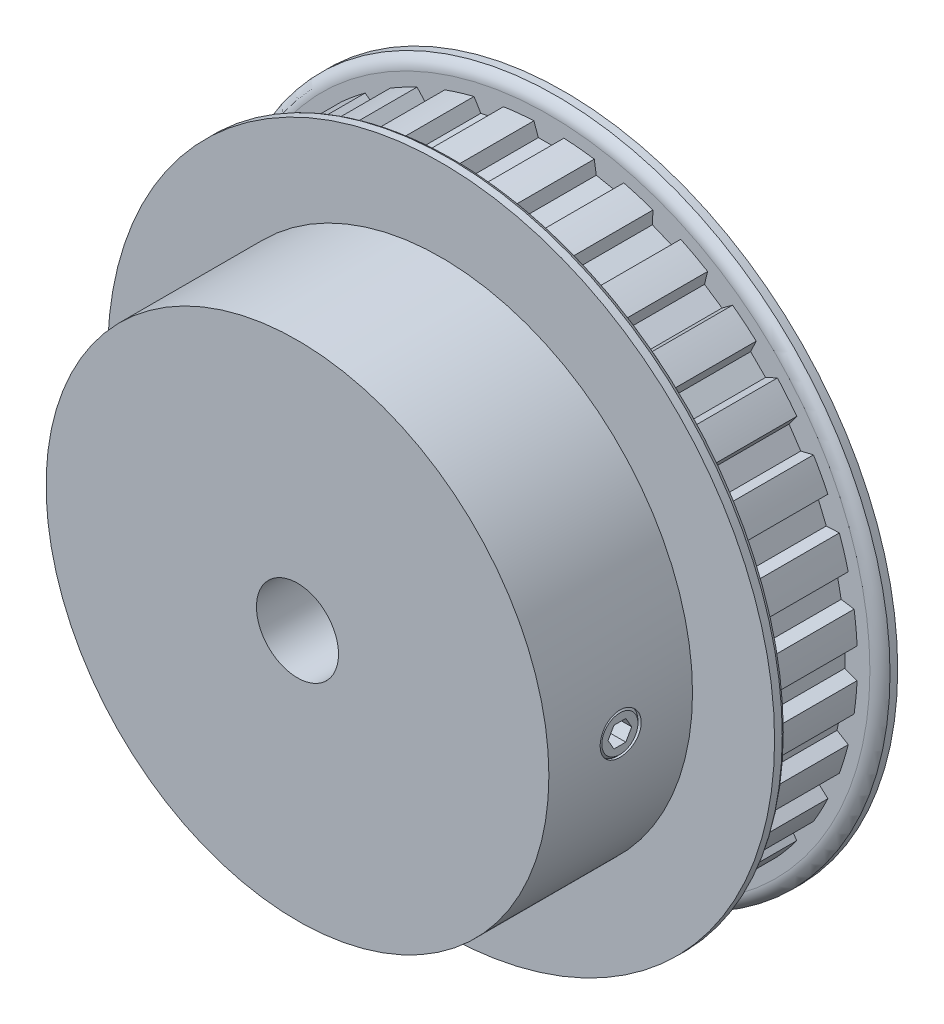
SolidWorks part; units mm, degrees
ref_plane "Front Plane" through (0, 0, 0) normal (0, 0, 1) x (1, 0, 0)
ref_plane "Top Plane" through (0, 0, 0) normal (0, 1, 0) x (1, 0, 0)
ref_plane "Right Plane" through (0, 0, 0) normal (1, 0, 0) x (0, 0, -1)
sketch "Sketch1" plane through (0, 0, 0) normal (0, 0, 1) x (1, 0, 0)
  line L0 (-2.3241, 47.6885) -> (-1.6307, 45.7835)
  line L1 (-1.6307, 45.7835) -> (1.6307, 45.7835)
  line L2 (1.6307, 45.7835) -> (2.3241, 47.6885)
  line L3 (-2.3241, 47.6885) -> (2.3241, 47.6885)
  line L4 (0, 0) -> (0, 45.7835) construction
  line L5 (0, 45.7835) -> (0, 49.3395) construction
  circle A0 centre (0, 0) radius 48.514 construction
  circle A1 centre (0, 0) radius 51.6001 construction
  circle A2 centre (0, 0) radius 47.7451 construction
  point P6 (0, 47.6885)
  point P11 (0, 48.514)
  point P13 (0, 51.6001)
  point P14 (0, 47.7451)
  dimension "D1" = 1.651
  dimension "D2" = 0.8255
sketch "Sketch2" plane through (0, 0, 0) normal (1, 0, 0) x (0, 0, -1)
  line L0 (-20.6375, 6.35) -> (20.6375, 6.35)
  line L1 (-20.6375, 6.35) -> (-20.6375, 38.9001)
  line L2 (-20.6375, 38.9001) -> (1.5875, 38.9001)
  line L3 (1.5875, 38.9001) -> (1.5875, 51.6001)
  line L4 (1.5875, 51.6001) -> (3.9624, 51.6001) construction
  line L5 (3.9624, 51.6001) -> (3.9624, 47.7451) construction
  line L6 (3.9624, 47.7451) -> (18.2626, 47.7451)
  line L7 (18.2626, 47.7451) -> (18.2626, 51.6001) construction
  line L8 (18.2626, 51.6001) -> (20.6375, 51.6001) construction
  line L9 (20.6375, 51.6001) -> (20.6375, 6.35)
  line L10 (-20.6375, 0) -> (20.6375, 0) construction
  line L13 (1.5875, 51.6001) -> (2.7749, 51.6001)
  line L14 (3.9624, 49.6726) -> (3.9624, 47.7451)
  line L15 (18.2626, 47.7451) -> (18.2626, 49.6726)
  line L16 (19.45, 51.6001) -> (20.6375, 51.6001)
  arc A0 (3.9624, 49.6726) -> (2.7749, 51.6001) centre (1.8043, 49.6726) ccw
  arc A1 (18.2626, 49.6726) -> (19.45, 51.6001) centre (20.4207, 49.6726) cw
  point P12 (3.9624, 49.6726)
  point P14 (2.7749, 51.6001)
  point P20 (18.2626, 49.6726)
  point P21 (19.45, 51.6001)
  point P25 (18.2626, 0)
  point P26 (3.9624, 0)
  point P27 (-1.3543, 27.3812)
  dimension "Bore" = 12.7
  dimension "Hub Dia" = 77.8002
  dimension "Outside Width" = 19.05
  dimension "Inside Width" = 14.3002
revolve "Revolve1" add sketch "Sketch2" angle 360 mid plane about L10
sketch "Sketch3" plane through (0, 0, 0) normal (0, 0, 1) x (1, 0, 0)
  line L0 (-1.6307, 45.7835) -> (1.6307, 45.7835) construction
  line L1 (1.6307, 45.7835) -> (2.3241, 47.6885) construction
  line L2 (-2.3241, 47.6885) -> (-1.6307, 45.7835) construction
  line L3 (-1.6307, 45.7835) -> (1.6307, 45.7835)
  line L4 (1.6307, 45.7835) -> (2.3241, 47.6885)
  line L5 (-2.3241, 47.6885) -> (-1.6307, 45.7835)
  circle A0 centre (0, 0) radius 47.7451 construction
  arc A1 (2.3241, 47.6885) -> (-2.3241, 47.6885) centre (0, 0) ccw
extrude "Cut-Extrude1" cut sketch "Sketch3" against normal up to vertex (18.2626 mm away) from vertex at -3.9624 starting at point (0, 47.7451, -3.9624)
pattern_circular "CirPattern1" count 32 over 360 about axis through (0, 0, 0) along (0, 0, 1) of "Cut-Extrude1"
sketch "Sketch4" plane through (0, 0, 0) normal (1, 0, 0) x (0, -1, 0)
  line L0 (0, 1.5875) -> (0, -20.6375) construction
  line L1 (-38.9001, 1.5875) -> (38.9001, 1.5875) construction
  line L2 (-38.9001, -20.6375) -> (38.9001, -20.6375) construction
  circle A0 centre (0, -9.525) radius 3.175
  dimension "D1" = 6.35
extrude "Cut-Extrude2" cut sketch "Sketch4" along normal through all
ref_plane "Plane1" through (0, 0, 9.525) normal (0, 0, 1) x (1, 0, 0)
sketch "Sketch5" plane through (0, 0, 9.525) normal (0, 0, 1) x (1, 0, 0)
  line L0 (0, 0.1664) -> (0, 38.9001) construction
  line L1 (6.35, -2.794) -> (6.35, 0)
  line L2 (6.731, -3.175) -> (38.3893, -3.175)
  line L3 (6.35, 0) -> (38.9001, 0) construction
  line L4 (6.35, 0) -> (38.7703, 0)
  line L5 (38.7703, 0) -> (38.7703, -2.794)
  line L6 (6.731, -3.175) -> (6.35, -2.794)
  line L7 (38.7703, -2.794) -> (38.3893, -3.175)
  circle A0 centre (0, 0) radius 38.9001 construction
  circle A1 centre (0, 0) radius 6.35 construction
  point P2 (6.35, -3.175)
  point P11 (38.7703, -3.175)
revolve "Revolve2" add sketch "Sketch5" angle 360 mid plane about L4
sketch "Sketch6" plane through (38.7703, 5.3841, 0) normal (-1, 0, 0) x (0, -1, 0)
  line L1 (5.3841, 11.3581) -> (3.7966, 10.4415)
  line L2 (3.7966, 10.4415) -> (3.7966, 8.6085)
  line L3 (3.7966, 8.6085) -> (5.3841, 7.6919)
  line L4 (5.3841, 7.6919) -> (6.9716, 8.6085)
  line L5 (6.9716, 8.6085) -> (6.9716, 10.4415)
  line L6 (6.9716, 10.4415) -> (5.3841, 11.3581)
  circle A0 centre (5.3841, 9.525) radius 1.5875 construction
  dimension "D1" = 3.175
extrude "Cut-Extrude3" cut sketch "Sketch6" along normal blind 2.3813
equation "\"D2@Sketch1\" = \"D1@Sketch1\"/2"
equation "\"D1@Sketch4\" = \"Bore@Sketch2\"/2"
equation "\"D1@Sketch6\" = \"D1@Sketch4\"/2"
equation "\"D1@Cut-Extrude3\" = \"D1@Sketch6\"*.75"
